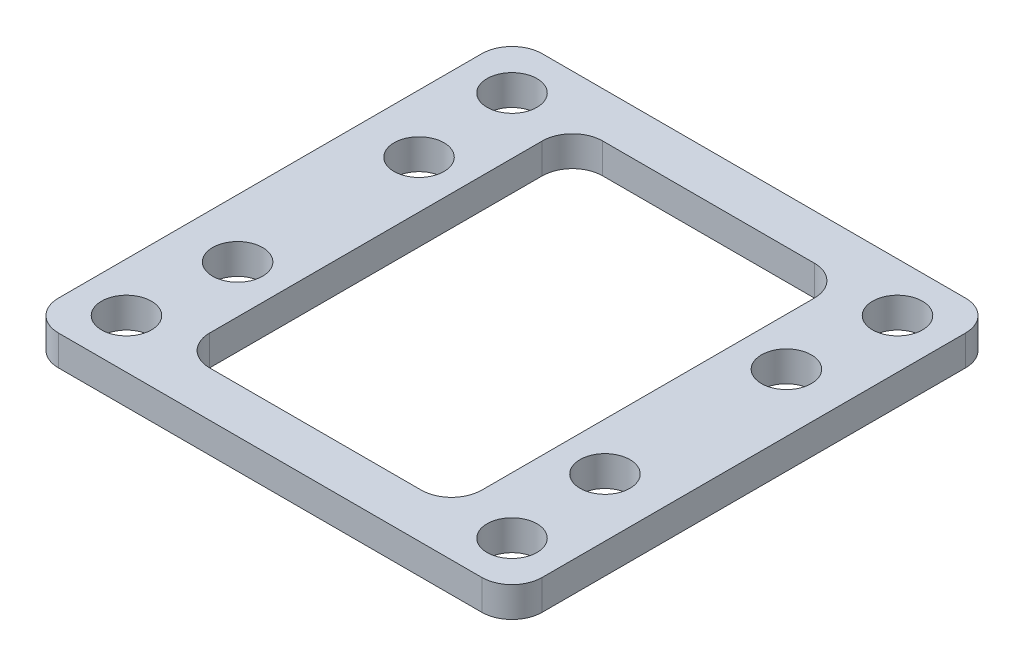
SolidWorks part; units mm, degrees
ref_plane "前视基准面" through (0, 0, 0) normal (0, 0, 1) x (1, 0, 0)
ref_plane "上视基准面" through (0, 0, 0) normal (0, 1, 0) x (1, 0, 0)
ref_plane "右视基准面" through (0, 0, 0) normal (1, 0, 0) x (0, 0, -1)
sketch "草图1" plane through (0, 0, 0) normal (0, 1, 0) x (1, 0, 0)
  line L1 (-16, 16) -> (16, 16)
  line L2 (-16, 16) -> (-16, -16)
  line L3 (-16, -16) -> (16, -16)
  line L4 (16, 16) -> (16, -16)
  line L5 (0, -16) -> (0, 16) construction
  line L6 (-16, 0) -> (16, 0) construction
  circle A0 centre (-12.75, 12.75) radius 1.65
  circle A1 centre (12.75, 12.75) radius 1.65
  circle A2 centre (12.75, -12.75) radius 1.65
  circle A3 centre (-12.75, -12.75) radius 1.65
  circle A4 centre (-12.15, 6) radius 1.65
  circle A6 centre (-12.15, -6) radius 1.65
  circle A7 centre (12.15, -6) radius 1.65
  circle A8 centre (12.15, 6) radius 1.65
  point P0 (0, 0)
  dimension "D1" = 25.5
  dimension "D2" = 3.3
  dimension "D5" = 25.5
  dimension "D6" = 24.3
  dimension "D7" = 12
  dimension "D8" = 3.3
  dimension "D3" = 32
  dimension "D4" = 32
extrude "凸台-拉伸1" add sketch "草图1" along normal blind 2
sketch "草图2" plane through (0, 2, 0) normal (0, 1, 0) x (1, 0, 0)
  line L0 (0, 16) -> (0, -16) construction
  line L1 (16, 16) -> (-16, 16) construction
  line L2 (-16, -16) -> (16, -16) construction
  line L3 (-16, 0) -> (16, 0) construction
  line L4 (-16, 16) -> (-16, -16) construction
  line L5 (16, -16) -> (16, 16) construction
  line L7 (9, -13) -> (-9, -13)
  line L8 (9, -13) -> (9, 13)
  line L9 (9, 13) -> (-9, 13)
  line L10 (-9, -13) -> (-9, 13)
  line L11 (0, 13) -> (0, -13) construction
  line L12 (9, 0) -> (-9, 0) construction
  point P5 (0, 0)
  dimension "D1" = 3
  dimension "D2" = 7
extrude "切除-拉伸1" cut sketch "草图2" against normal through all
fillet "圆角1" radius 2 8 edges at (16, 1, -16) (-16, 1, -16) (-16, 1, 16) (16, 1, 16) (9, 1, 13) (-9, 1, 13) (9, 1, -13) (-9, 1, -13)
equation "\"m\"= 2"
